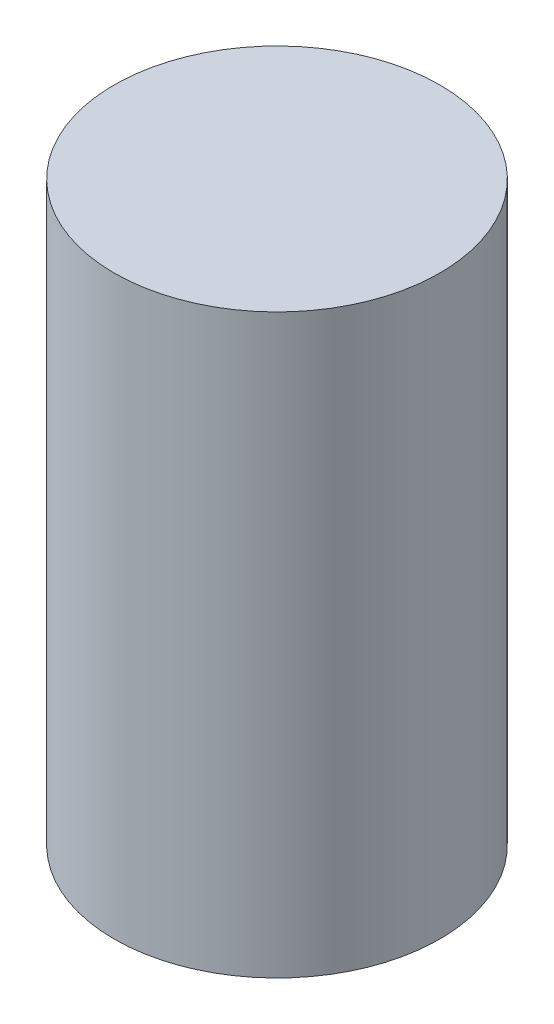
SolidWorks part; units mm, degrees
ref_plane "Спереди" through (0, 0, 0) normal (0, 0, 1) x (1, 0, 0)
ref_plane "Сверху" through (0, 0, 0) normal (0, 1, 0) x (1, 0, 0)
ref_plane "Справа" through (0, 0, 0) normal (1, 0, 0) x (0, 0, -1)
sketch "Эскиз1" plane through (0, 0, 0) normal (0, 1, 0) x (1, 0, 0)
  circle A0 centre (0, 0) radius 19.625
  dimension "D1" = 39.25
extrude "Бобышка-Вытянуть1" add sketch "Эскиз1" along normal blind 69.5
hole_wizard "Отверстие обработанное метчиком M51" positions "Эскиз2" profile "Эскиз3" tap size "M5" standard "ISO"
sketch "Эскиз2" plane through (0, 0, 0) normal (0, -1, 0) x (-1, 0, 0)
  point P0 (0, 0)
sketch "Эскиз3" plane through (0, 0, 0) normal (1, 0, 0) x (0, 0, -1)
  line L0 (0, 0) -> (0, 15.2618)
  line L1 (0, 15.2618) -> (2.1, 14)
  line L2 (2.1, 14) -> (2.1, 0)
  line L5 (2.1, 0) -> (0, 0)
  line L10 (0, 15.2618) -> (-2.1, 14) construction
  line L11 (0, -6.35) -> (0, 107.95) construction
  dimension "Диаметр сверла" = 4.2
  dimension "Глубина сверла" = 14
  dimension "Угол заточки сверла" = 118
cosmetic thread "Отверстие резьбы1" parameters "D1"=10, "D2"=5
